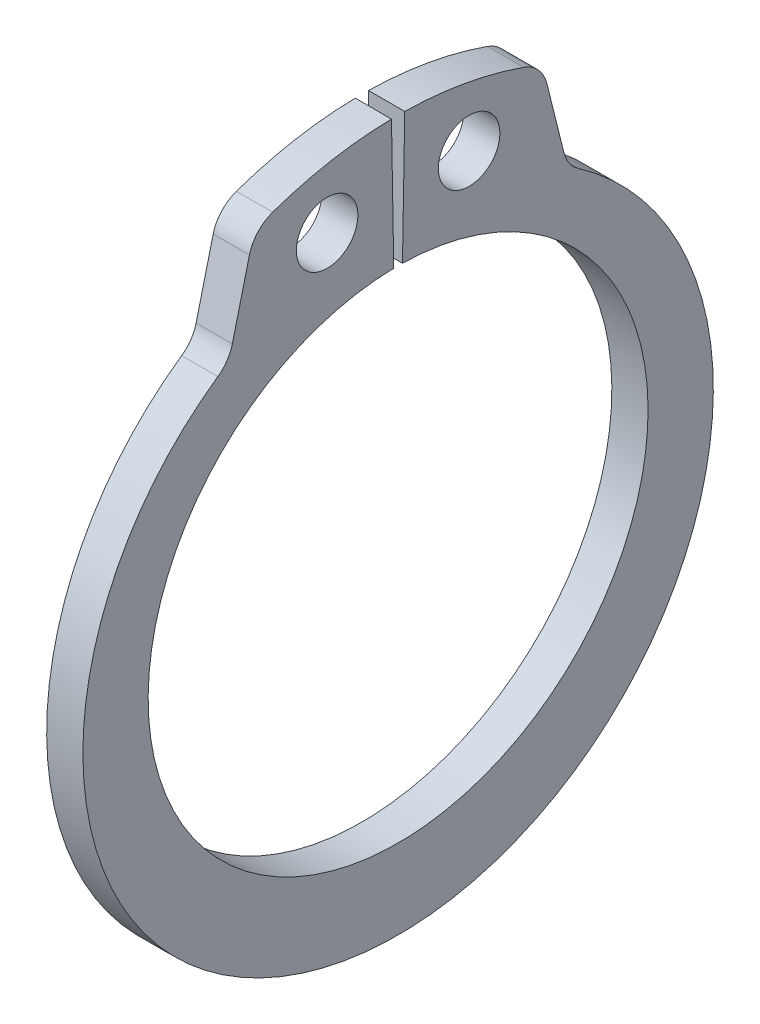
SolidWorks part; units mm, degrees
material "Cast Carbon Steel"
ref_plane "Front" through (0, 0, 0) normal (0, 0, 1) x (1, 0, 0)
ref_plane "Top" through (0, 0, 0) normal (0, 1, 0) x (1, 0, 0)
ref_plane "Right" through (0, 0, 0) normal (1, 0, 0) x (0, 0, -1)
sketch "Sketch1" plane through (0, 0, 0) normal (1, 0, 0) x (0, 0, -1)
  line L0 (0, 0) -> (0, 6.9) construction
  line L1 (-0.1204, 6.8989) -> (-0.1833, 10.4984)
  line L2 (-0.1833, 10.4984) -> (-3.7988, 10.4353) construction
  line L3 (-3.7988, 10.4353) -> (-4.6698, 6.9422) construction
  line L4 (0.1833, 10.4984) -> (0.1204, 6.8989)
  line L5 (0.1833, 10.4984) -> (3.7988, 10.4353) construction
  line L6 (3.7988, 10.4353) -> (4.6698, 6.9422) construction
  line L7 (-4.6698, 6.9422) -> (-3.8512, 5.7253) construction
  line L8 (4.6698, 6.9422) -> (3.8512, 5.7253) construction
  line L9 (0, -6.9) -> (0, -9.1) construction
  line L10 (-3.7988, 10.4353) -> (-0.1204, 6.8989) construction
  line L11 (-6.9, 0) -> (6.9, 0) construction
  line L12 (0, 6.9) -> (0, 10.5) construction
  line L13 (3.9778, 9.7173) -> (4.6698, 6.9422)
  line L14 (-3.9778, 9.7173) -> (-4.6698, 6.9422)
  circle A0 centre (0, 0) radius 6.9 construction
  arc A1 (-0.1204, 6.8989) -> (0.1204, 6.8989) centre (0, 0) ccw
  circle A2 centre (0, -0.3992) radius 8.7008 construction
  circle A4 centre (-1.9596, 8.6671) radius 0.85
  circle A5 centre (1.9596, 8.6671) radius 0.85
  arc A6 (-4.6698, 6.9422) -> (4.6698, 6.9422) centre (0, -0.3992) ccw
  arc A7 (0.1833, 10.4984) -> (3.9778, 9.7173) centre (0, 0) cw
  arc A8 (-0.1833, 10.4984) -> (-3.9778, 9.7173) centre (0, 0) ccw
  dimension "A" = 13.8
  dimension "Hole" = 1.7
  dimension "Smin" = 1.4667
  dimension "D1" = 75
  dimension "Angle" = 1
  dimension "H" = 3.6
extrude "Extrude1" add sketch "Sketch1" along normal mid plane 1
fillet "Fillet1" radius 1 4 edges at (0, 6.9422, 4.6698) (0, 9.7173, 3.9778) (0, 9.7173, -3.9778) (0, 6.9422, -4.6698)
sketch "Sketch2" plane through (0, 0, 0) normal (0, 0, 1) x (1, 0, 0)
  line L0 (-2.75, 0) -> (8.25, 0)
  line L1 (8.25, 0) -> (8.25, -7.5)
  line L2 (-2.75, 0) -> (-2.75, -7.15)
  line L3 (8.25, -7.5) -> (0.55, -7.5)
  line L4 (0.55, -7.5) -> (0.55, -7.15)
  line L5 (0.55, -7.15) -> (-0.55, -7.15)
  line L6 (-0.55, -7.15) -> (-0.55, -7.5)
  line L7 (-0.55, -7.5) -> (-2.75, -7.5) construction
  line L8 (-2.75, -7.5) -> (-2.75, 0) construction
  line L9 (0, -7.15) -> (0, 0) construction
  line L10 (8.25, 0) -> (14.0551, 0) construction
  line L11 (-2.75, -7.15) -> (-2.4, -7.5)
  line L12 (-2.4, -7.5) -> (-0.55, -7.5)
  dimension "D2" = 11
  dimension "D3" = 2.75
  dimension "D1" = 45
revolve "Revolve1" [suppressed] add sketch "Sketch2" angle 360 about L10
equation "\"D2@Sketch2\" = \"W@Sketch2\"*10"
equation "\"D3@Sketch2\" = \"D2@Sketch2\"/4"
equation "\"Smin@Sketch1\" = \"Smax@Sketch1\"/1.5"
equation "\"D1@Fillet1\" = \"D1@Extrude1\""
